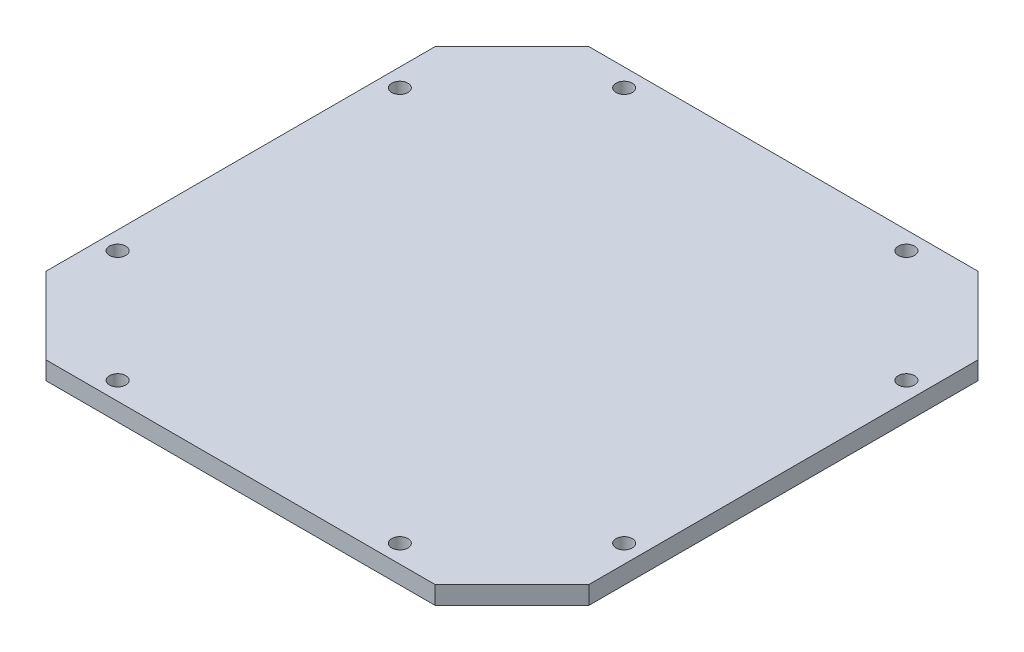
SolidWorks part; units mm, degrees
ref_plane "Front Plane" through (0, 0, 0) normal (0, 0, 1) x (1, 0, 0)
ref_plane "Top Plane" through (0, 0, 0) normal (0, 1, 0) x (1, 0, 0)
ref_plane "Right Plane" through (0, 0, 0) normal (1, 0, 0) x (0, 0, -1)
sketch "Sketch2" plane through (0, 0, 0) normal (0, 1, 0) x (1, 0, 0)
  line L0 (0, -150) -> (0, 150) construction
  line L1 (-150, 0) -> (150, 0) construction
  line L2 (107.5736, 150) -> (-107.5736, 150)
  line L3 (-107.5736, 150) -> (-150, 107.5736)
  line L4 (107.5736, 150) -> (150, 107.5736)
  line L5 (-150, 107.5736) -> (-150, -107.5736)
  line L6 (150, 107.5736) -> (150, -107.5736)
  line L7 (-150, -107.5736) -> (-107.5736, -150)
  line L8 (150, -107.5736) -> (107.5736, -150)
  line L9 (-107.5736, -150) -> (107.5736, -150)
  line L10 (140, 78) -> (140, 0) construction
  line L11 (-140, 78) -> (-140, 0) construction
  line L12 (140, 0) -> (140, -78) construction
  line L13 (-140, 0) -> (-140, -78) construction
  circle A0 centre (-78, 140) radius 4.5
  circle A1 centre (78, 140) radius 4.5
  circle A2 centre (-140, 78) radius 4.5
  circle A3 centre (140, 78) radius 4.5
  circle A4 centre (-140, -78) radius 4.5
  circle A5 centre (140, -78) radius 4.5
  circle A6 centre (-78, -140) radius 4.5
  circle A7 centre (78, -140) radius 4.5
  point P4 (0, 0)
  point P7 (0, 0)
  dimension "D4" = 9
  dimension "D6" = 62
  dimension "D7" = 62
  dimension "D8" = 280
  dimension "D9" = 62
  dimension "D1" = 300
  dimension "D2" = 60
  dimension "D3" = 45
  dimension "D5" = 156
extrude "Boss-Extrude1" add sketch "Sketch2" along normal mid plane 10
